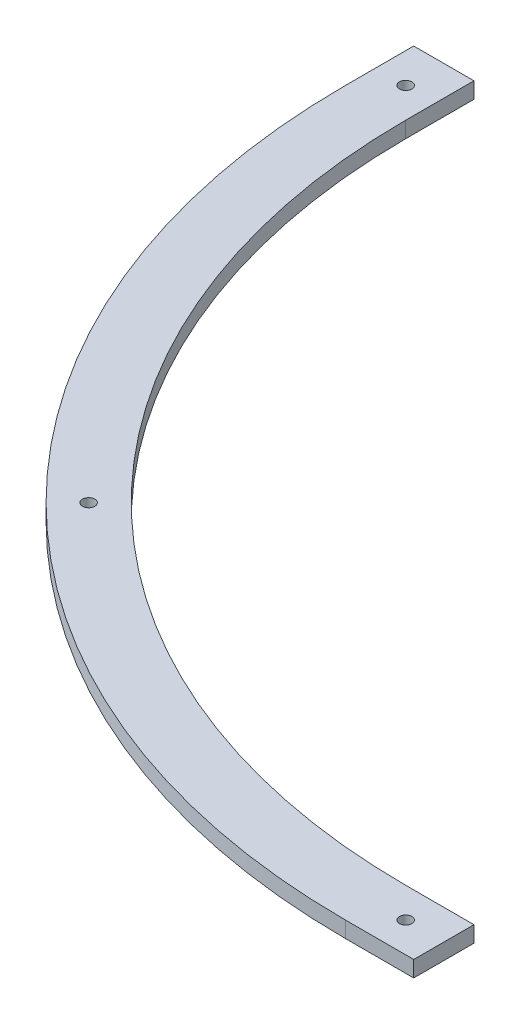
SolidWorks part; units mm, degrees
ref_plane "Front Plane" through (0, 0, 0) normal (0, 0, 1) x (1, 0, 0)
ref_plane "Top Plane" through (0, 0, 0) normal (0, 1, 0) x (1, 0, 0)
ref_plane "Right Plane" through (0, 0, 0) normal (1, 0, 0) x (0, 0, -1)
sketch "Sketch1" plane through (0, 0, 0) normal (0, 1, 0) x (1, 0, 0)
  line L0 (-82.5, 107) -> (-82.5, 90) construction
  line L1 (-90, -90) -> (90, -90) construction
  line L2 (-90, -90) -> (-90, 90) construction
  line L3 (-90, 90) -> (90, 90) construction
  line L4 (90, -90) -> (90, 90) construction
  line L5 (-90, -90) -> (90, 90) construction
  line L6 (-90, 90) -> (90, -90) construction
  line L8 (-90, 90) -> (-90, 107)
  line L9 (-90, 107) -> (-75, 107)
  line L10 (-75, 90) -> (-75, 107)
  line L11 (90, -75) -> (107, -75)
  line L13 (90, -90) -> (107, -90)
  line L14 (107, -75) -> (107, -90)
  line L15 (90, -82.5) -> (107, -82.5) construction
  arc A0 (-90, 90) -> (90, -90) centre (90, 90) ccw
  arc A1 (-75, 90) -> (90, -75) centre (90, 90) ccw
  arc A2 (-81.6603, 107) -> (107, -81.6603) centre (90, 90) ccw construction
  circle A3 centre (-82.5, 97.5) radius 1.55
  circle A4 centre (97.5, -82.5) radius 1.55
  circle A5 centre (-31.9759, -31.9759) radius 1.55
  point P0 (0, 0)
  dimension "D2" = 330
  dimension "D3" = 345
  dimension "D5" = 3.1
  dimension "D7" = 3.1
  dimension "D9" = 3.1
  dimension "D1" = 180
  dimension "D4" = 17
  dimension "D6" = 7.5
  dimension "D8" = 7.5
extrude "Boss-Extrude1" add sketch "Sketch1" along normal blind 4
